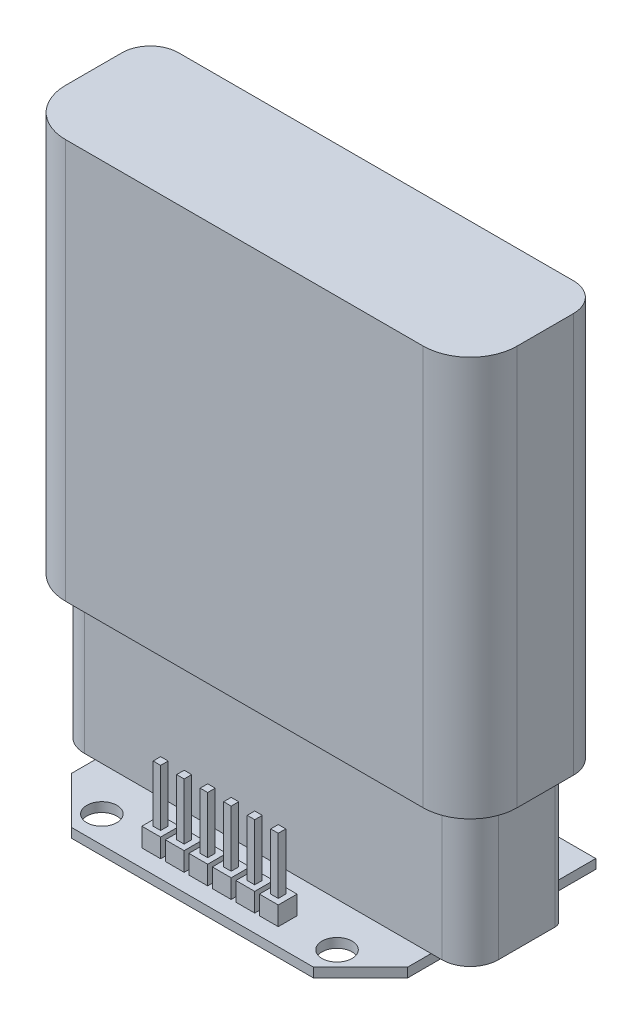
SolidWorks part; units mm, degrees
ref_plane "前视基准面" through (0, 0, 0) normal (0, 0, 1) x (1, 0, 0)
ref_plane "上视基准面" through (0, 0, 0) normal (0, 1, 0) x (1, 0, 0)
ref_plane "右视基准面" through (0, 0, 0) normal (1, 0, 0) x (0, 0, -1)
sketch "草图1" plane through (0, 0, 0) normal (0, 1, 0) x (1, 0, 0)
  line L1 (17.85, -12.5) -> (-17.85, -12.5)
  line L2 (17.85, -12.5) -> (17.85, 12.5)
  line L3 (17.85, 12.5) -> (-17.85, 12.5)
  line L4 (-17.85, -12.5) -> (-17.85, 12.5)
  line L5 (17.85, -12.5) -> (-17.85, 12.5) construction
  line L6 (17.85, 12.5) -> (-17.85, -12.5) construction
  point P0 (0, 0)
  dimension "D1" = 35.7
  dimension "D2" = 25
extrude "凸台-拉伸1" add sketch "草图1" along normal blind 1
sketch "草图2" plane through (0, 1, 0) normal (0, 1, 0) x (1, 0, 0)
  line L1 (24, -7) -> (-24, -7)
  line L2 (24, -7) -> (24, 7)
  line L3 (24, 7) -> (-24, 7)
  line L4 (-24, -7) -> (-24, 7)
  line L5 (24, -7) -> (-24, 7) construction
  line L6 (24, 7) -> (-24, -7) construction
  point P0 (0, 0)
  dimension "D1" = 48
  dimension "D2" = 14
extrude "凸台-拉伸2" add sketch "草图2" along normal blind 57.5
fillet "圆角1" radius 3 2 edges at (24, 29.75, -7) (-24, 29.75, -7)
fillet "圆角2" radius 5 2 edges at (-24, 29.75, 7) (24, 29.75, 7)
chamfer "倒角1" distance 5 angle 45 2 edges at (17.85, 0.5, 12.5) (-17.85, 0.5, 12.5)
hole_wizard "M3 间隙孔1" positions "草图3" profile "草图4" hole size "M3" standard "GB" end condition up to next
sketch "草图3" plane through (0, 0, 0) normal (0, -1, 0) x (-1, 0, 0)
  line L0 (0, 0) -> (0, -9.65) construction
  line L2 (0, 0) -> (4.6381, 0) construction
  point P0 (0, 9.65)
  point P2 (-12.5, -9.65)
  point P4 (12.5, -9.65)
  dimension "D1" = 25
  dimension "D2" = 19.3
sketch "草图4" plane through (0, 0, -9.65) normal (1, 0, 0) x (0, 0, -1)
  line L0 (0, 0) -> (0, 1)
  line L1 (0, 1) -> (1.6, 1)
  line L2 (1.6, 1) -> (1.6, 0)
  line L5 (1.6, 0) -> (0, 0)
  line L11 (0, -6.35) -> (0, 107.95) construction
  dimension "通孔孔直径" = 3.2
  dimension "通孔孔深度" = 1
sketch "草图5" plane through (0, 1, 0) normal (0, -1, 0) x (1, 0, 0)
  line L0 (-22, 2) -> (-22, -4)
  line L1 (-21, -5) -> (21, -5)
  line L2 (22, -4) -> (22, 2)
  line L3 (19, 5) -> (-19, 5)
  line L4 (-24, 2) -> (-24, -4)
  line L5 (19, 7) -> (-19, 7)
  line L6 (24, -4) -> (24, 2)
  line L7 (-21, -7) -> (21, -7)
  line L8 (-24, 2) -> (-24, -4)
  line L9 (19, 7) -> (-19, 7)
  line L10 (24, -4) -> (24, 2)
  line L11 (-21, -7) -> (21, -7)
  arc A0 (-22, -4) -> (-21, -5) centre (-21, -4) ccw
  arc A1 (21, -5) -> (22, -4) centre (21, -4) ccw
  arc A2 (22, 2) -> (19, 5) centre (19, 2) ccw
  arc A3 (-19, 5) -> (-22, 2) centre (-19, 2) ccw
  arc A4 (-19, 7) -> (-24, 2) centre (-19, 2) ccw
  arc A5 (24, 2) -> (19, 7) centre (19, 2) ccw
  arc A6 (21, -7) -> (24, -4) centre (21, -4) ccw
  arc A7 (-24, -4) -> (-21, -7) centre (-21, -4) ccw
  arc A8 (-19, 7) -> (-24, 2) centre (-19, 2) ccw
  arc A9 (24, 2) -> (19, 7) centre (19, 2) ccw
  arc A10 (21, -7) -> (24, -4) centre (21, -4) ccw
  arc A11 (-24, -4) -> (-21, -7) centre (-21, -4) ccw
  dimension "D1" = 0
  dimension "D2" = 2
extrude "切除-拉伸1" cut sketch "草图5" against normal blind 15
sketch "草图6" plane through (0, 1, 0) normal (0, 1, 0) x (1, 0, 0)
  line L0 (0, 0) -> (0, -10.65) construction
  line L1 (2.25, -10.65) -> (0.25, -10.65)
  line L2 (2.25, -10.65) -> (2.25, -8.65)
  line L3 (2.25, -8.65) -> (0.25, -8.65)
  line L4 (0.25, -10.65) -> (0.25, -8.65)
  line L5 (2.25, -10.65) -> (0.25, -8.65) construction
  line L6 (2.25, -8.65) -> (0.25, -10.65) construction
  line L8 (-2.25, -8.65) -> (-0.25, -10.65) construction
  line L9 (-2.25, -10.65) -> (-0.25, -8.65) construction
  line L10 (-0.25, -10.65) -> (-0.25, -8.65)
  line L11 (-2.25, -8.65) -> (-0.25, -8.65)
  line L12 (-2.25, -10.65) -> (-2.25, -8.65)
  line L13 (-2.25, -10.65) -> (-0.25, -10.65)
  line L14 (-2.5, -11.2821) -> (-2.5, -7.4972) construction
  line L15 (-2.75, -10.65) -> (-4.75, -8.65) construction
  line L16 (-2.75, -8.65) -> (-4.75, -10.65) construction
  line L17 (-7.25, -8.65) -> (-5.25, -10.65) construction
  line L18 (-7.25, -10.65) -> (-5.25, -8.65) construction
  line L19 (-2.75, -10.65) -> (-4.75, -10.65)
  line L20 (-2.75, -10.65) -> (-2.75, -8.65)
  line L21 (-2.75, -8.65) -> (-4.75, -8.65)
  line L22 (-4.75, -10.65) -> (-4.75, -8.65)
  line L23 (-5.25, -10.65) -> (-5.25, -8.65)
  line L24 (-7.25, -8.65) -> (-5.25, -8.65)
  line L25 (-7.25, -10.65) -> (-7.25, -8.65)
  line L26 (-7.25, -10.65) -> (-5.25, -10.65)
  line L27 (7.25, -10.65) -> (5.25, -8.65) construction
  line L28 (7.25, -8.65) -> (5.25, -10.65) construction
  line L29 (2.75, -8.65) -> (4.75, -10.65) construction
  line L30 (2.75, -10.65) -> (4.75, -8.65) construction
  line L31 (7.25, -10.65) -> (5.25, -10.65)
  line L32 (7.25, -10.65) -> (7.25, -8.65)
  line L33 (7.25, -8.65) -> (5.25, -8.65)
  line L34 (5.25, -10.65) -> (5.25, -8.65)
  line L35 (4.75, -10.65) -> (4.75, -8.65)
  line L36 (2.75, -8.65) -> (4.75, -8.65)
  line L37 (2.75, -10.65) -> (2.75, -8.65)
  line L38 (2.75, -10.65) -> (4.75, -10.65)
  point P0 (1.25, -9.65)
  point P9 (12.5, -9.65)
  point P15 (-1.25, -9.65)
  point P26 (-3.75, -9.65)
  point P27 (-6.25, -9.65)
  point P36 (6.25, -9.65)
  point P37 (3.75, -9.65)
  dimension "D1" = 2
  dimension "D2" = 2
  dimension "D3" = 0.25
  dimension "D4" = 0.5
extrude "凸台-拉伸3" add sketch "草图6" along normal blind 8
sketch "草图7" plane through (0, 9, 0) normal (0, 1, 0) x (1, 0, 0)
  line L0 (7.25, -10.65) -> (7.25, -8.65) construction
  line L1 (7.25, -8.65) -> (5.25, -8.65) construction
  line L2 (5.25, -8.65) -> (5.25, -10.65) construction
  line L3 (5.25, -10.65) -> (7.25, -10.65) construction
  line L4 (-7.25, -8.65) -> (-7.25, -10.65)
  line L5 (-7.25, -10.65) -> (-5.25, -10.65)
  line L6 (-5.25, -10.65) -> (-5.25, -8.65)
  line L7 (-5.25, -8.65) -> (-7.25, -8.65)
  line L8 (-7.25, -8.65) -> (-7.25, -10.65)
  line L9 (-7.25, -10.65) -> (-5.25, -10.65)
  line L10 (-5.25, -10.65) -> (-5.25, -8.65)
  line L11 (-5.25, -8.65) -> (-7.25, -8.65)
  line L12 (2.75, -8.65) -> (2.75, -10.65) construction
  line L13 (2.75, -10.65) -> (4.75, -10.65) construction
  line L14 (4.75, -10.65) -> (4.75, -8.65) construction
  line L15 (4.75, -8.65) -> (2.75, -8.65) construction
  line L16 (0.25, -8.65) -> (0.25, -10.65) construction
  line L17 (0.25, -10.65) -> (2.25, -10.65) construction
  line L18 (2.25, -10.65) -> (2.25, -8.65) construction
  line L19 (2.25, -8.65) -> (0.25, -8.65) construction
  line L20 (-2.25, -8.65) -> (-2.25, -10.65) construction
  line L21 (-2.25, -10.65) -> (-0.25, -10.65) construction
  line L22 (-0.25, -10.65) -> (-0.25, -8.65) construction
  line L23 (-0.25, -8.65) -> (-2.25, -8.65) construction
  line L24 (-2.75, -10.65) -> (-2.75, -8.65) construction
  line L25 (-2.75, -8.65) -> (-4.75, -8.65) construction
  line L26 (-4.75, -8.65) -> (-4.75, -10.65) construction
  line L27 (-4.75, -10.65) -> (-2.75, -10.65) construction
  line L28 (7.25, -10.65) -> (7.25, -8.65)
  line L29 (7.25, -8.65) -> (5.25, -8.65)
  line L30 (5.25, -8.65) -> (5.25, -10.65)
  line L31 (5.25, -10.65) -> (7.25, -10.65)
  line L32 (2.75, -8.65) -> (2.75, -10.65)
  line L33 (2.75, -10.65) -> (4.75, -10.65)
  line L34 (4.75, -10.65) -> (4.75, -8.65)
  line L35 (4.75, -8.65) -> (2.75, -8.65)
  line L36 (0.25, -8.65) -> (0.25, -10.65)
  line L37 (0.25, -10.65) -> (2.25, -10.65)
  line L38 (2.25, -10.65) -> (2.25, -8.65)
  line L39 (2.25, -8.65) -> (0.25, -8.65)
  line L40 (-2.25, -8.65) -> (-2.25, -10.65)
  line L41 (-2.25, -10.65) -> (-0.25, -10.65)
  line L42 (-0.25, -10.65) -> (-0.25, -8.65)
  line L43 (-0.25, -8.65) -> (-2.25, -8.65)
  line L44 (-2.75, -10.65) -> (-2.75, -8.65)
  line L45 (-2.75, -8.65) -> (-4.75, -8.65)
  line L46 (-4.75, -8.65) -> (-4.75, -10.65)
  line L47 (-4.75, -10.65) -> (-2.75, -10.65)
  line L48 (-6.65, -9.25) -> (-6.65, -10.05)
  line L49 (-6.65, -10.05) -> (-5.85, -10.05)
  line L50 (-5.85, -10.05) -> (-5.85, -9.25)
  line L51 (-5.85, -9.25) -> (-6.65, -9.25)
  line L52 (6.65, -10.05) -> (6.65, -9.25)
  line L53 (6.65, -9.25) -> (5.85, -9.25)
  line L54 (5.85, -9.25) -> (5.85, -10.05)
  line L55 (5.85, -10.05) -> (6.65, -10.05)
  line L56 (3.35, -9.25) -> (3.35, -10.05)
  line L57 (3.35, -10.05) -> (4.15, -10.05)
  line L58 (4.15, -10.05) -> (4.15, -9.25)
  line L59 (4.15, -9.25) -> (3.35, -9.25)
  line L60 (0.85, -9.25) -> (0.85, -10.05)
  line L61 (0.85, -10.05) -> (1.65, -10.05)
  line L62 (1.65, -10.05) -> (1.65, -9.25)
  line L63 (1.65, -9.25) -> (0.85, -9.25)
  line L64 (-1.65, -9.25) -> (-1.65, -10.05)
  line L65 (-1.65, -10.05) -> (-0.85, -10.05)
  line L66 (-0.85, -10.05) -> (-0.85, -9.25)
  line L67 (-0.85, -9.25) -> (-1.65, -9.25)
  line L68 (-3.35, -10.05) -> (-3.35, -9.25)
  line L69 (-3.35, -9.25) -> (-4.15, -9.25)
  line L70 (-4.15, -9.25) -> (-4.15, -10.05)
  line L71 (-4.15, -10.05) -> (-3.35, -10.05)
  dimension "D1" = 0
  dimension "D2" = 0.6
extrude "切除-拉伸2" cut sketch "草图7" against normal blind 6
